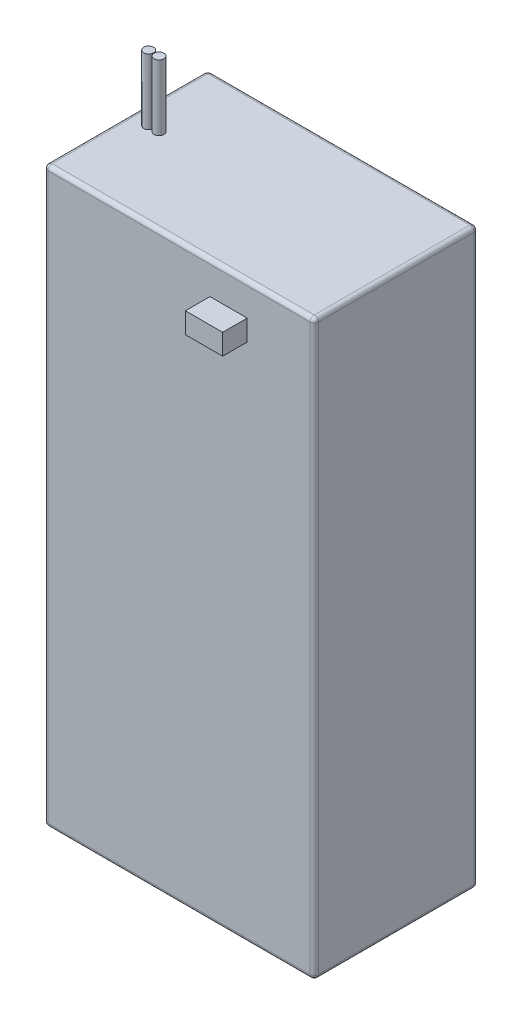
SolidWorks part; units mm, degrees
ref_plane "Front" through (0, 0, 0) normal (0, 0, 1) x (1, 0, 0)
ref_plane "Top" through (0, 0, 0) normal (0, 1, 0) x (1, 0, 0)
ref_plane "Right" through (0, 0, 0) normal (1, 0, 0) x (0, 0, -1)
sketch "Sketch1" plane through (0, 0, 0) normal (0, 0, 1) x (1, 0, 0)
  line L1 (-16.5, -35) -> (16.5, -35)
  line L2 (-16.5, -35) -> (-16.5, 35)
  line L3 (-16.5, 35) -> (16.5, 35)
  line L4 (16.5, -35) -> (16.5, 35)
  line L5 (-16.5, -35) -> (16.5, 35) construction
  line L6 (-16.5, 35) -> (16.5, -35) construction
  point P0 (0, 0)
  dimension "D1" = 70
  dimension "D2" = 33
extrude "Boss-Extrude1" add sketch "Sketch1" along normal blind 20
fillet "Fillet1" radius 0.5 12 edges at (-16.5, -35, 10) (16.5, -35, 10) (16.5, 35, 10) (-16.5, 35, 10) (0, 35, 0) (-16.5, 0, 0) (0, -35, 0) (16.5, 0, 0) (0, -35, 20) (-16.5, 0, 20) (0, 35, 20) (16.5, 0, 20)
sketch "Sketch2" plane through (0, 35, 0) normal (0, 1, 0) x (1, 0, 0)
  circle A0 centre (-14.1249, -9.5918) radius 0.6
  circle A1 centre (-12.8648, -9.5918) radius 0.6
  dimension "D1" = 1.2
extrude "Wires" add sketch "Sketch2" along normal blind 8
sketch "Sketch3" plane through (0, 0, 20) normal (0, 0, 1) x (1, 0, 0)
  line L1 (3.7669, 31.0762) -> (8.3175, 31.0762)
  line L2 (3.7669, 31.0762) -> (3.7669, 28.5481)
  line L3 (3.7669, 28.5481) -> (8.3175, 28.5481)
  line L4 (8.3175, 31.0762) -> (8.3175, 28.5481)
  line L5 (3.7669, 31.0762) -> (8.3175, 28.5481) construction
  line L6 (3.7669, 28.5481) -> (8.3175, 31.0762) construction
  point P0 (6.0422, 29.8121)
extrude "Power Switch" add sketch "Sketch3" along normal blind 3
